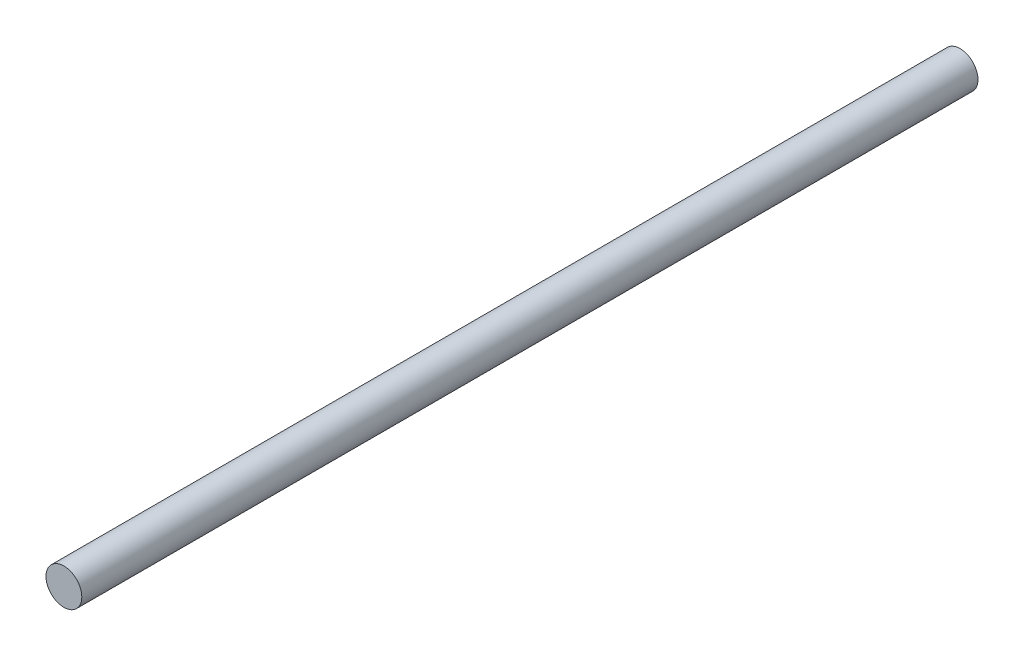
SolidWorks part; units mm, degrees
ref_plane "Front Plane" through (0, 0, 0) normal (0, 0, 1) x (1, 0, 0)
ref_plane "Top Plane" through (0, 0, 0) normal (0, 1, 0) x (1, 0, 0)
ref_plane "Right Plane" through (0, 0, 0) normal (1, 0, 0) x (0, 0, -1)
sketch "Sketch2" plane through (0, 0, 0) normal (0, 0, 1) x (1, 0, 0)
  circle A0 centre (0, 0) radius 4
extrude "Boss-Extrude1" add sketch "Sketch2" along normal mid plane 200
